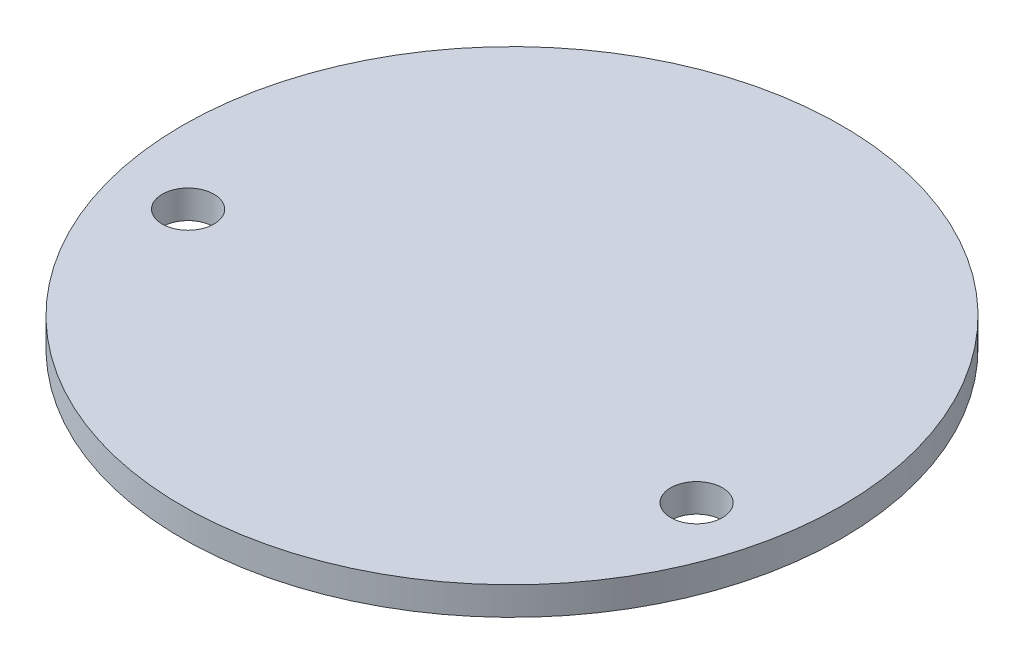
SolidWorks part; units mm, degrees
material "A-Glass Fiber"
ref_plane "Front Plane" through (0, 0, 0) normal (0, 0, 1) x (1, 0, 0)
ref_plane "Top Plane" through (0, 0, 0) normal (0, 1, 0) x (1, 0, 0)
ref_plane "Right Plane" through (0, 0, 0) normal (1, 0, 0) x (0, 0, -1)
sketch "Sketch2" plane through (0, 0, 0) normal (0, 0, 1) x (1, 0, 0)
  line L0 (0, -417.1122) -> (0, 20438.4966) construction
  line L1 (0, 0) -> (35, 0)
  line L2 (35, 0) -> (35, 3)
  line L5 (35, 3) -> (0, 3)
  line L6 (0, 3) -> (0, 0)
  point P5 (35, 1.236)
  dimension "D1" = 3
  dimension "D4" = 70
revolve "Revolve1" add sketch "Sketch2" angle 360 about L0
sketch "Sketch4" plane through (0, 3, 0) normal (0, 1, 0) x (1, 0, 0)
  line L0 (-27, -7.4) -> (27, -7.4) construction
  circle A0 centre (-27, -7.4) radius 2.75
  circle A1 centre (27, -7.4) radius 2.75
  point P4 (0, -7.4)
  dimension "D3" = 5.5
  dimension "D1" = 54
  dimension "D2" = 7.4
extrude "Cut-Extrude2" cut sketch "Sketch4" against normal up to next
sketch "Sketch3" plane through (0, 3, 0) normal (0, 1, 0) x (1, 0, 0)
  line L0 (-13.5, 15) -> (13.5, 15) construction
  circle A0 centre (-13.5, 15) radius 3.25
  circle A1 centre (13.5, 15) radius 3.25
  point P4 (0, 15)
  dimension "D1" = 6.5
  dimension "D2" = 27
  dimension "D3" = 15
extrude "Cut-Extrude1" [suppressed] cut sketch "Sketch3" against normal up to next
